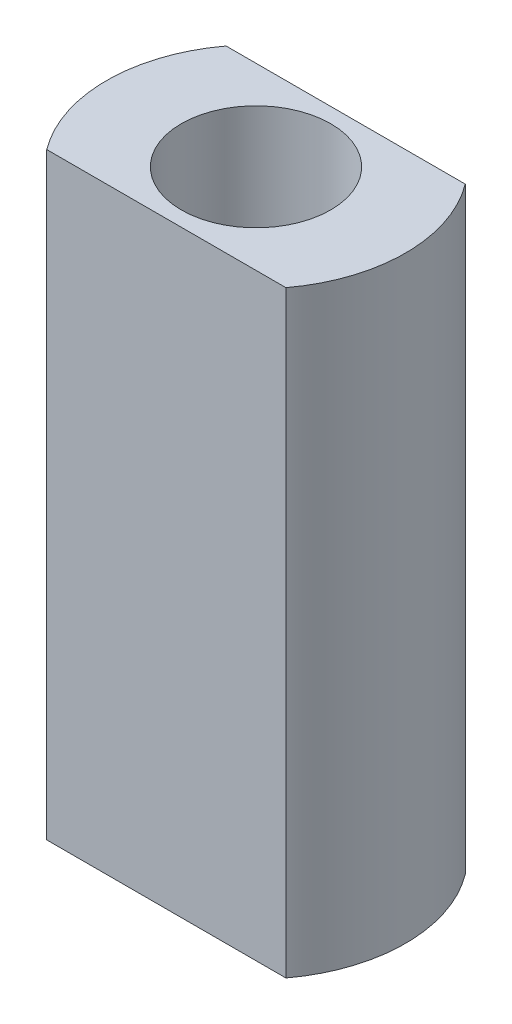
SolidWorks part; units mm, degrees
ref_plane "Piano frontale" through (0, 0, 0) normal (0, 0, 1) x (1, 0, 0)
ref_plane "Piano superiore" through (0, 0, 0) normal (0, 1, 0) x (1, 0, 0)
ref_plane "Piano destro" through (0, 0, 0) normal (1, 0, 0) x (0, 0, -1)
sketch "Schizzo1" plane through (0, 0, 0) normal (0, 1, 0) x (1, 0, 0)
  line L0 (-4, 3) -> (4, 3)
  line L1 (4, 3) -> (4, -3)
  line L2 (4, -3) -> (-4, -3)
  line L3 (-4, -3) -> (-4, 3)
  circle A0 centre (0, 0) radius 5
  dimension "D1" = 10
  dimension "D2" = 6
extrude "Estrusione-Estrusione1" add sketch "Schizzo1" along normal blind 20 contours L3 A0 | L3 L2 L1 L0 | L1 A0
sketch "Schizzo2" plane through (0, 20, 0) normal (0, 1, 0) x (1, 0, 0)
  circle A0 centre (0, 0) radius 2.5
  dimension "D1" = 5
extrude "Taglio-Estrusione1" cut sketch "Schizzo2" against normal blind 20
